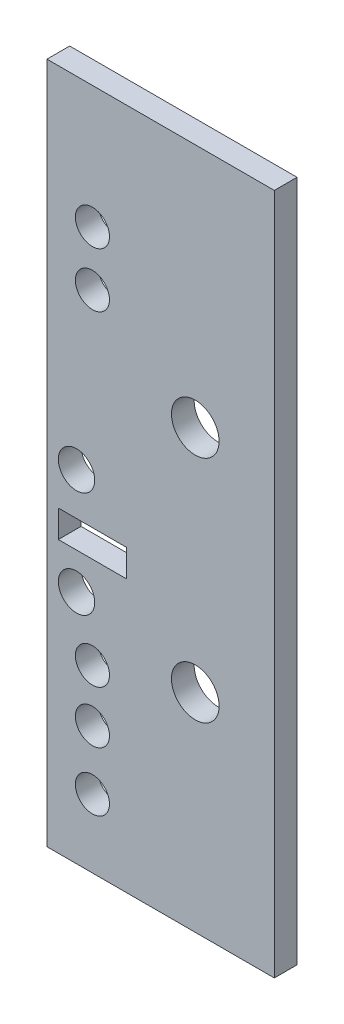
SolidWorks part; units mm, degrees
ref_plane "前视基准面" through (0, 0, 0) normal (0, 0, 1) x (1, 0, 0)
ref_plane "上视基准面" through (0, 0, 0) normal (0, 1, 0) x (1, 0, 0)
ref_plane "右视基准面" through (0, 0, 0) normal (1, 0, 0) x (0, 0, -1)
other "Configuration Table"
sketch "草图1" plane through (0, 0, 0) normal (0, 0, 1) x (1, 0, 0)
  line L1 (-23.3216, 41.8115) -> (26.6784, 41.8115)
  line L2 (-23.3216, 41.8115) -> (-23.3216, -108.1885)
  line L3 (-23.3216, -108.1885) -> (26.6784, -108.1885)
  line L4 (26.6784, 41.8115) -> (26.6784, -108.1885)
  dimension "D1" = 50
  dimension "D2" = 150
extrude "凸台-拉伸1" add sketch "草图1" along normal blind 5
sketch "草图2" plane through (0, 0, 5) normal (0, 0, 1) x (1, 0, 0)
  line L0 (-23.3216, -108.1885) -> (26.6784, -108.1885) construction
  line L1 (-23.3216, 41.8115) -> (-23.3216, -108.1885) construction
  circle A0 centre (-13.3216, -93.1885) radius 3.75
  circle A1 centre (-13.3216, -80.1885) radius 3.75
  circle A2 centre (-13.3216, -68.6485) radius 3.75
  circle A3 centre (-13.3216, 2.8495) radius 3.75
  circle A4 centre (-13.3216, 14.8635) radius 3.75
  point P0 (-13.3216, -93.1885)
  point P5 (-13.3216, -80.1885)
  point P6 (-13.3216, -68.6485)
  point P7 (-13.3216, 2.8495)
  point P8 (-13.3216, 14.8635)
  dimension "D7" = 10
  dimension "D1" = 15
  dimension "D2" = 10
  dimension "D3" = 13
  dimension "D4" = 24.54
  dimension "D5" = 96.038
  dimension "D6" = 12.014
extrude "切除-拉伸1" cut sketch "草图2" against normal blind 5
sketch "草图3" plane through (0, 0, 5) normal (0, 0, 1) x (1, 0, 0)
  line L0 (-23.3216, 41.8115) -> (-23.3216, -108.1885) construction
  circle A0 centre (-13.3216, -68.6485) radius 3.75 construction
  circle A1 centre (-16.8216, -56.4299) radius 4
  circle A2 centre (-16.8216, -33.1399) radius 4
  point P0 (-16.8216, -56.4299)
  point P3 (-16.8216, -33.1399)
  dimension "D1" = 6.5
  dimension "D2" = 12.71
  dimension "D3" = 23.29
extrude "切除-拉伸2" cut sketch "草图3" against normal blind 5
sketch "草图4" plane through (0, 0, 5) normal (0, 0, 1) x (1, 0, 0)
  line L0 (-23.3216, 41.8115) -> (-23.3216, -108.1885) construction
  line L1 (-20.8216, -42.4299) -> (-5.8216, -42.4299)
  line L2 (-20.8216, -42.4299) -> (-20.8216, -48.4299)
  line L3 (-20.8216, -48.4299) -> (-5.8216, -48.4299)
  line L4 (-5.8216, -42.4299) -> (-5.8216, -48.4299)
  circle A1 centre (-16.8216, -56.4299) radius 4 construction
  dimension "D1" = 15
  dimension "D2" = 8
  dimension "D3" = 6
  dimension "D4" = 2.5
extrude "切除-拉伸3" cut sketch "草图4" against normal blind 5
sketch "草图5" plane through (0, 0, 5) normal (0, 0, 1) x (1, 0, 0)
  circle A0 centre (9.2955, -12.0603) radius 5.24
  circle A1 centre (9.2955, -62.4779) radius 5.24
extrude "切除-拉伸4" cut sketch "草图5" against normal blind 5
